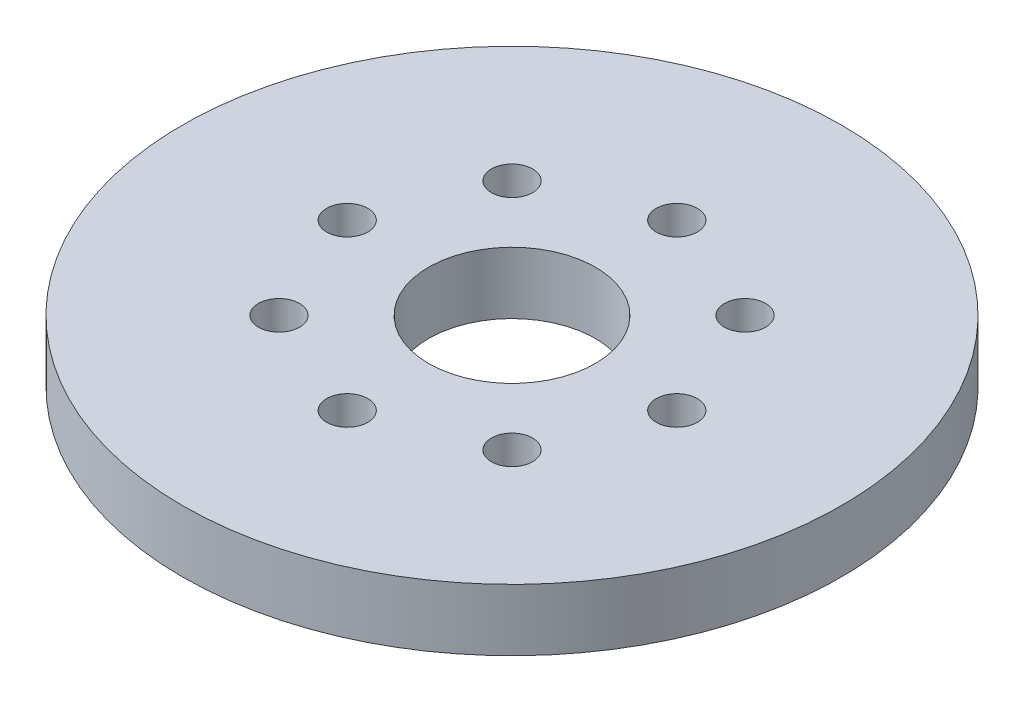
SolidWorks part; units mm, degrees
ref_plane "Front Plane" through (0, 0, 0) normal (0, 0, 1) x (1, 0, 0)
ref_plane "Top Plane" through (0, 0, 0) normal (0, 1, 0) x (1, 0, 0)
ref_plane "Right Plane" through (0, 0, 0) normal (1, 0, 0) x (0, 0, -1)
sketch "Sketch1" plane through (0, 0, 0) normal (0, 1, 0) x (1, 0, 0)
  circle A1 centre (0, 0) radius 4.05
  circle A2 centre (0, 0) radius 16
  circle A3 centre (0, 8) radius 1
  circle A4 centre (5.6569, 5.6569) radius 1
  circle A5 centre (8, 0) radius 1
  circle A6 centre (5.6569, -5.6569) radius 1
  circle A7 centre (0, -8) radius 1
  circle A8 centre (-5.6569, -5.6569) radius 1
  circle A9 centre (-8, 0) radius 1
  circle A10 centre (-5.6569, 5.6569) radius 1
  dimension "D1" = 8
  dimension "D3" = 8.1
  dimension "D4" = 2
extrude "Boss-Extrude1" add sketch "Sketch1" along normal blind 3
